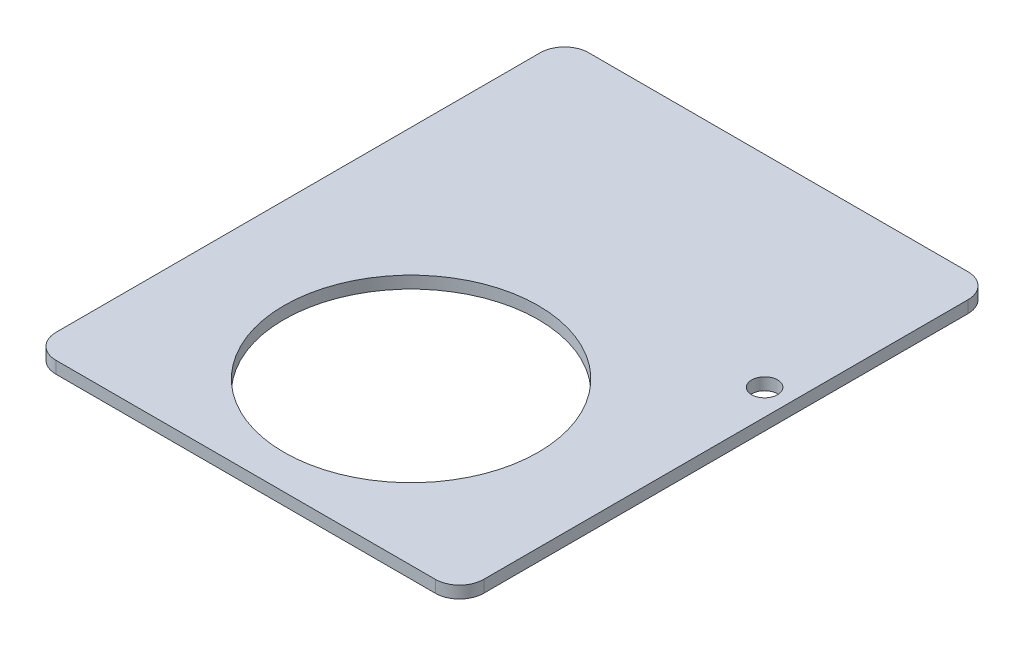
SolidWorks part; units mm, degrees
ref_plane "Front Plane" through (0, 0, 0) normal (0, 0, 1) x (1, 0, 0)
ref_plane "Top Plane" through (0, 0, 0) normal (0, 1, 0) x (1, 0, 0)
ref_plane "Right Plane" through (0, 0, 0) normal (1, 0, 0) x (0, 0, -1)
sketch "Sketch1" plane through (0, 0, 0) normal (0, 1, 0) x (1, 0, 0)
  line L1 (-17.8909, 47.1512) -> (29.1091, 47.1512)
  line L2 (-20.8909, 44.1512) -> (-20.8909, -15.8488)
  line L3 (-17.8909, -18.8488) -> (29.1091, -18.8488)
  line L4 (32.1091, 44.1512) -> (32.1091, -15.8488)
  arc A0 (-20.8909, -15.8488) -> (-17.8909, -18.8488) centre (-17.8909, -15.8488) ccw
  arc A1 (29.1091, -18.8488) -> (32.1091, -15.8488) centre (29.1091, -15.8488) ccw
  arc A2 (32.1091, 44.1512) -> (29.1091, 47.1512) centre (29.1091, 44.1512) ccw
  arc A3 (-17.8909, 47.1512) -> (-20.8909, 44.1512) centre (-17.8909, 44.1512) ccw
  circle A4 centre (6.1091, 1.1512) radius 15.75
  circle A5 centre (28.9091, 22.1512) radius 1.6
  point P6 (-20.8909, -18.8488)
  point P9 (32.1091, -18.8488)
  point P12 (32.1091, 47.1512)
  dimension "D3" = 3
  dimension "D4" = 31.5
  dimension "D6" = 3.2
  dimension "D1" = 53
  dimension "D2" = 66
  dimension "D5" = 26
  dimension "D7" = 25
  dimension "D8" = 3.2
  dimension "D9" = 20
extrude "Boss-Extrude2" add sketch "Sketch1" along normal blind 1.5
